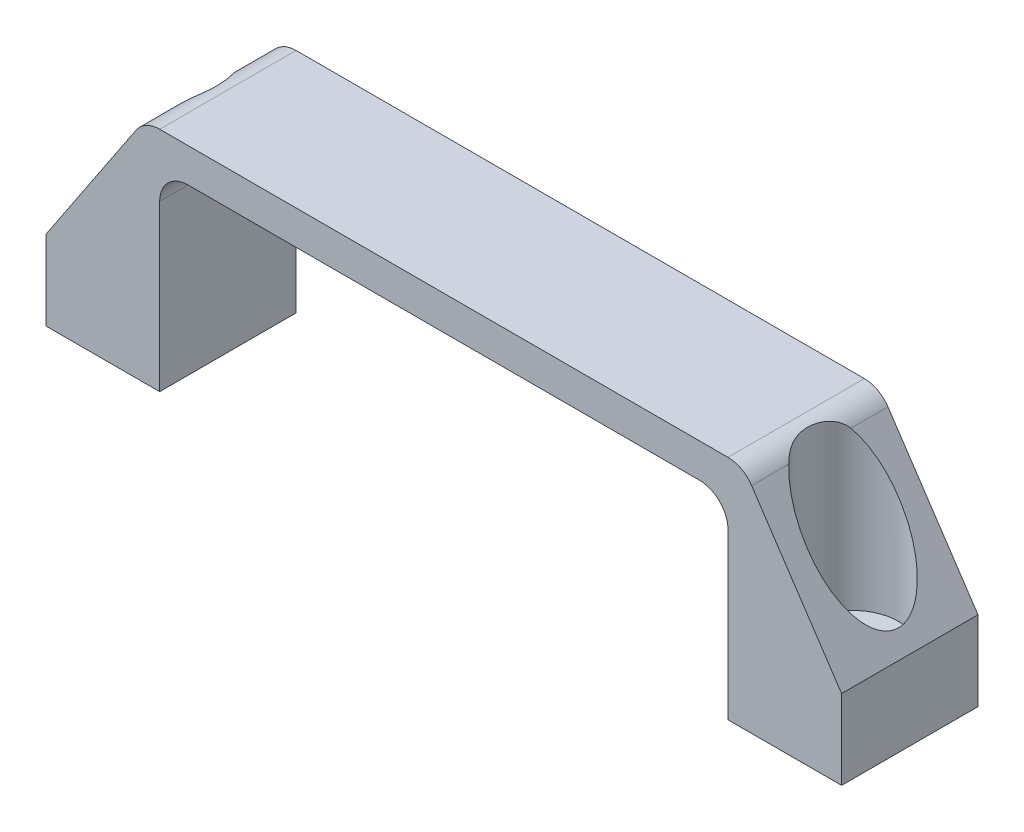
SolidWorks part; units mm, degrees
ref_plane "前视基准面" through (0, 0, 0) normal (0, 0, 1) x (1, 0, 0)
ref_plane "上视基准面" through (0, 0, 0) normal (0, 1, 0) x (1, 0, 0)
ref_plane "右视基准面" through (0, 0, 0) normal (1, 0, 0) x (0, 0, -1)
sketch "草图1" plane through (0, 0, 0) normal (0, 0, 1) x (1, 0, 0)
  line L0 (0, 0) -> (0, 14)
  line L1 (0, 14) -> (15.839, 37.7724)
  line L2 (20, 40) -> (120, 40)
  line L7 (115, 34) -> (25, 34)
  line L8 (20, 29) -> (20, 0)
  line L9 (20, 0) -> (0, 0)
  line L10 (70, 40) -> (70, 34) construction
  line L11 (120, 0) -> (140, 0)
  line L12 (120, 29) -> (120, 0)
  line L13 (140, 14) -> (124.161, 37.7724)
  line L14 (140, 0) -> (140, 14)
  arc A0 (120, 29) -> (115, 34) centre (115, 29) ccw
  arc A1 (25, 34) -> (20, 29) centre (25, 29) ccw
  arc A2 (124.161, 37.7724) -> (120, 40) centre (120, 35) ccw
  arc A3 (20, 40) -> (15.839, 37.7724) centre (20, 35) ccw
  point P13 (9.6407, 40)
  point P16 (120, 34)
  point P19 (20, 34)
  point P22 (122.6768, 40)
  point P25 (17.3232, 40)
  point P26 (0, 7)
  dimension "D4" = 5
  dimension "D5" = 5
  dimension "D1" = 140
  dimension "D2" = 40
  dimension "D3" = 6
  dimension "D6" = 14
  dimension "D7" = 20
  dimension "D8" = 100
extrude "凸台-拉伸1" add sketch "草图1" against normal blind 24
sketch "草图2" plane through (0, 0, 0) normal (0, -1, 0) x (1, 0, 0)
  line L0 (0, -12) -> (20, -12) construction
  line L1 (0, -24) -> (0, 0) construction
  line L2 (20, -24) -> (20, 0) construction
  line L3 (120, -12) -> (140, -12) construction
  line L4 (120, -24) -> (120, 0) construction
  line L5 (140, -24) -> (140, 0) construction
  circle A0 centre (10, -12) radius 4.5
  circle A1 centre (130, -12) radius 4.5
  dimension "D2" = 9
  dimension "D1" = 120
extrude "切除-拉伸1" cut sketch "草图2" against normal blind 20 and the other way through all
sketch "草图3" plane through (0, 20, 0) normal (0, -1, 0) x (1, 0, 0)
  circle A0 centre (130, -12) radius 8
  circle A1 centre (10, -12) radius 8
  dimension "D1" = 16
extrude "切除-拉伸2" cut sketch "草图3" against normal blind 24 and the other way blind 10
